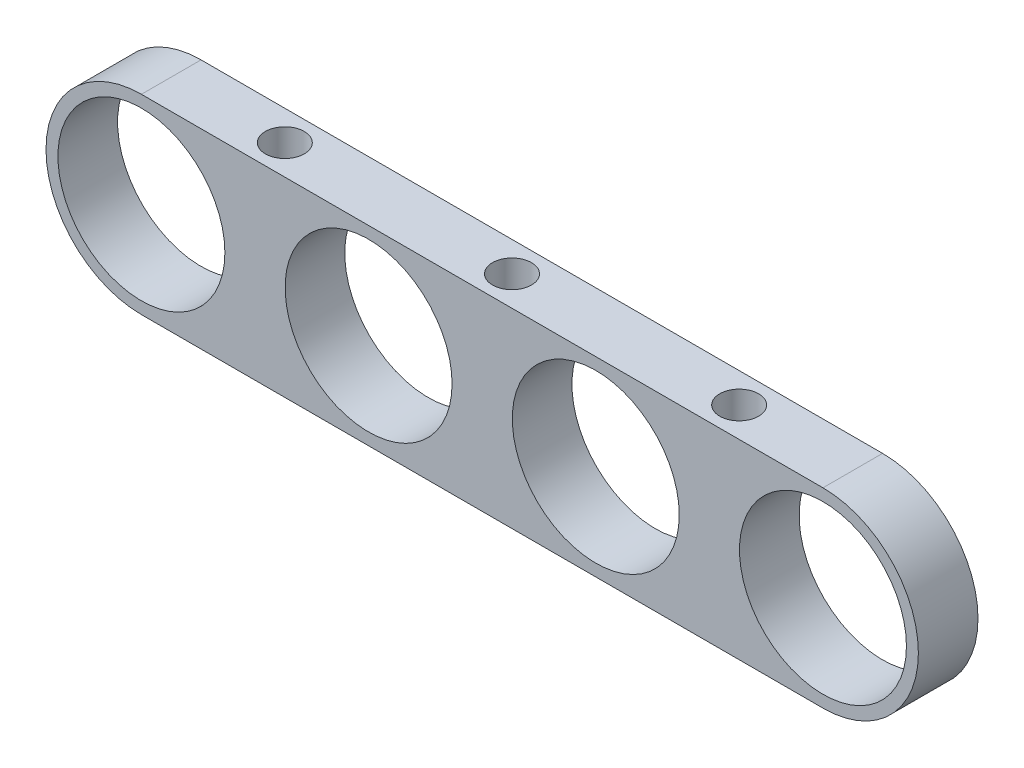
SolidWorks part; units mm, degrees
ref_plane "Front Plane" through (0, 0, 0) normal (0, 0, 1) x (1, 0, 0)
ref_plane "Top Plane" through (0, 0, 0) normal (0, 1, 0) x (1, 0, 0)
ref_plane "Right Plane" through (0, 0, 0) normal (1, 0, 0) x (0, 0, -1)
sketch "Sketch1" plane through (0, 0, 0) normal (0, 0, 1) x (1, 0, 0)
  line L0 (0, 16) -> (114.3, 16)
  line L1 (0, -16) -> (114.3, -16)
  circle A0 centre (0, 0) radius 14
  circle A1 centre (38.1, 0) radius 14
  circle A2 centre (76.2, 0) radius 14
  circle A3 centre (114.3, 0) radius 14
  arc A6 (114.3, -16) -> (114.3, 16) centre (114.3, 0) ccw
  arc A7 (0, 16) -> (0, -16) centre (0, 0) ccw
  circle A8 centre (152.4, 0) radius 14 [skipped]
  dimension "D1" = 5
  dimension "D2" = 28
  dimension "D3" = 16
  dimension "D4" = 38.1
  dimension "D5" = 0
extrude "Boss-Extrude1" add sketch "Sketch1" along normal blind 10
sketch "Sketch3" plane through (0, 16, 0) normal (0, 1, 0) x (1, 0, 0)
  line L0 (114.3, 0) -> (0, 0) construction
  line L1 (0, -10) -> (0, 0) construction
  circle A0 centre (19.05, -5) radius 3.2634
  dimension "D1" = 5
  dimension "D2" = 19.05
extrude "Cut-Extrude1" cut sketch "Sketch3" against normal blind 10
sketch "Sketch4" plane through (0, 6, 0) normal (0, 1, 0) x (1, 0, 0)
  circle A0 centre (19.05, -5) radius 1.5875
  dimension "D1" = 3.175
extrude "Cut-Extrude2" cut sketch "Sketch4" against normal through all
pattern_linear "LPattern1" count 3 spacing 38.1 along (1, 0, 0) of "Cut-Extrude1", "Cut-Extrude2"
